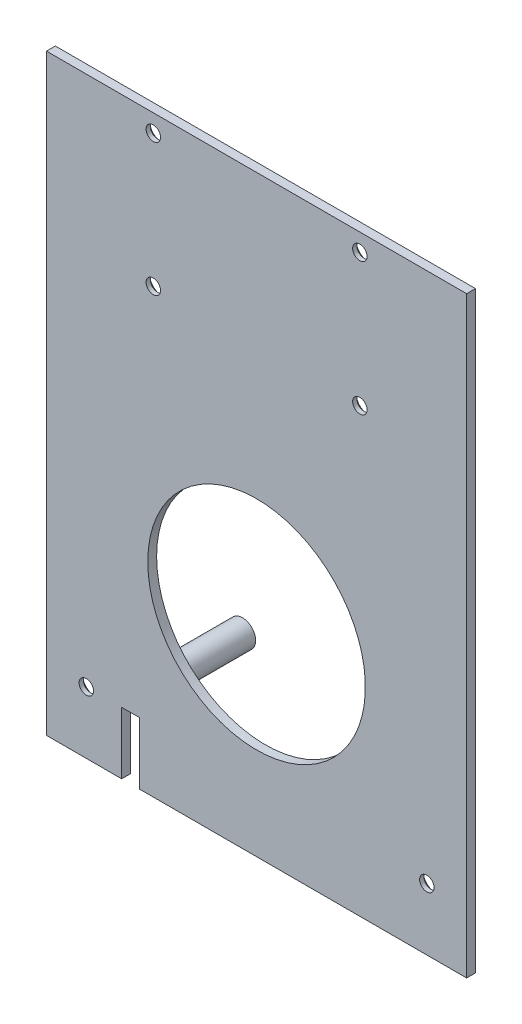
SolidWorks part; units mm, degrees
ref_plane "Front Plane" through (0, 0, 0) normal (0, 0, 1) x (1, 0, 0)
ref_plane "Top Plane" through (0, 0, 0) normal (0, 1, 0) x (1, 0, 0)
ref_plane "Right Plane" through (0, 0, 0) normal (1, 0, 0) x (0, 0, -1)
sketch "Sketch1" plane through (0, 0, 0) normal (0, 0, 1) x (1, 0, 0)
  line L1 (0, 0) -> (95, 0)
  line L2 (0, 0) -> (0, 134)
  line L3 (0, 134) -> (95, 134)
  line L4 (95, 0) -> (95, 134)
  dimension "D1" = 95
  dimension "D2" = 134
extrude "Boss-Extrude1" add sketch "Sketch1" along normal blind 2
sketch "Sketch6" plane through (0, 0, 0) normal (0, 0, -1) x (-1, 0, 0)
  line L0 (-47.5, 0) -> (-47.5, 134) construction
  line L1 (0, 0) -> (-95, 0) construction
  line L2 (-95, 134) -> (0, 134) construction
  line L3 (-86, 14) -> (-9, 14) construction
  line L4 (-70.85, 100) -> (-24.15, 100) construction
  line L6 (-70.85, 130) -> (-24.15, 130) construction
  point P10 (-47.5, 14)
  point P13 (-47.5, 100)
  point P14 (-47.5, 130)
  dimension "D1" = 46.7
  dimension "D2" = 46.7
  dimension "D3" = 77
  dimension "D4" = 14
  dimension "D5" = 100
  dimension "D6" = 30
hole_wizard "CSK for #4 Flat Head Machine Screw (100)2" positions "Sketch7" profile "Sketch8" countersink size "#4" standard "Superior" end condition through all
sketch "Sketch7" plane through (0, 0, 0) normal (0, 0, -1) x (-1, 0, 0)
  point P0 (-70.85, 130)
  point P3 (-24.15, 130)
  point P6 (-24.15, 100)
  point P9 (-70.85, 100)
  point P12 (-86, 14)
  point P15 (-9, 14)
sketch "Sketch8" plane through (70.85, 130, 0) normal (1, 0, 0) x (0, 1, 0)
  line L0 (0, 0) -> (0, 2)
  line L1 (0, 2) -> (1.632, 2)
  line L2 (1.632, 2) -> (1.6319, 1.0284)
  line L3 (1.6319, 1.0284) -> (2.8575, 0)
  line L5 (2.8575, 0) -> (0, 0)
  line L6 (-1.6319, 1.0284) -> (-2.8575, 0) construction
  line L11 (0, -6.35) -> (0, 107.95) construction
  dimension "Thru Hole Dia." = 3.2639
  dimension "Thru Hole Depth" = 2
  dimension "Near C'Sink Dia." = 5.715
  dimension "Near C'Sink Angle" = 100
sketch "Sketch12" plane through (0, 0, 2) normal (0, 0, 1) x (1, 0, 0)
  line L0 (47.5, 0) -> (47.5, 134) construction
  line L1 (0, 0) -> (95, 0) construction
  circle A0 centre (47.5, 52.5) radius 35
  dimension "D2" = 70
  dimension "D1" = 52.5
sketch "Sketch13" plane through (0, 0, 0) normal (0, 0, -1) x (-1, 0, 0)
  line L0 (-47.5, 0) -> (-47.5, 134) construction
  line L1 (0, 0) -> (-95, 0) construction
  circle A0 centre (-47.5, 45.5) radius 24.6
  dimension "D1" = 49.2
  dimension "D2" = 45.5
extrude "Cut-Extrude2" cut sketch "Sketch13" against normal through all
sketch "Sketch14" plane through (0, 0, 0) normal (0, 0, -1) x (-1, 0, 0)
  line L0 (-72, 70.1) -> (-23, 70.1) construction
  line L1 (-23, 20.9) -> (-72, 20.9) construction
  line L2 (-47.5, 0) -> (-47.5, 134) construction
  circle A1 centre (-47.5, 45.5) radius 24.6 construction
  circle A2 centre (-72, 70.1) radius 3
  circle A3 centre (-23, 70.1) radius 3
  circle A4 centre (-72, 20.9) radius 3
  circle A5 centre (-23, 20.9) radius 3
  point P4 (-47.5, 20.9)
  point P9 (-47.5, 70.1)
  dimension "D3" = 6
  dimension "D1" = 49
  dimension "D2" = 49
extrude "Boss-Extrude4" add sketch "Sketch14" along normal blind 19.3
sketch "Sketch15" plane through (0, 0, -19.3) normal (0, 0, -1) x (-1, 0, 0)
  circle A0 centre (-72, 70.1) radius 1.15
  circle A1 centre (-23, 70.1) radius 1.15
  circle A2 centre (-23, 20.9) radius 1.15
  circle A3 centre (-72, 20.9) radius 1.15
  dimension "D1" = 2.3
extrude "Cut-Extrude3" cut sketch "Sketch15" against normal blind 15
sketch "Sketch16" plane through (0, 0, 0) normal (0, 0, -1) x (-1, 0, 0)
  line L0 (0, 0) -> (-95, 0) construction
  line L1 (-17, 0) -> (-21, 0)
  line L2 (-17, 0) -> (-17, 14)
  line L3 (-17, 14) -> (-21, 14)
  line L4 (-21, 0) -> (-21, 14)
  line L5 (-47.5, 0) -> (-47.5, 134) construction
  dimension "D1" = 30.5
  dimension "D2" = 4
  dimension "D3" = 14
extrude "Cut-Extrude4" cut sketch "Sketch16" against normal through all
